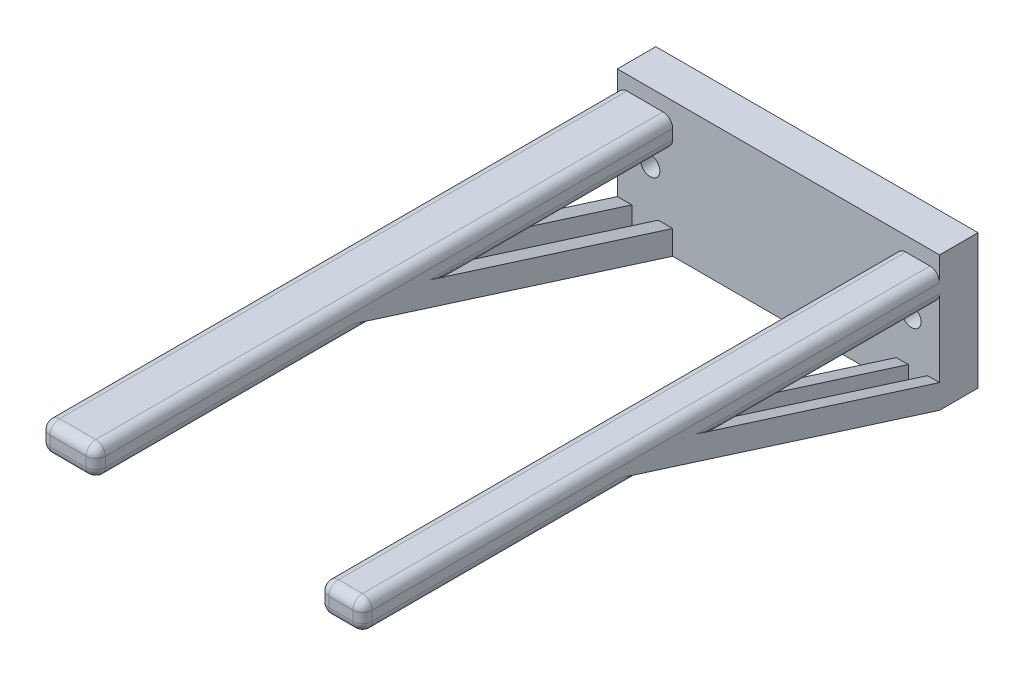
SolidWorks part; units mm, degrees
ref_plane "Plan de face" through (0, 0, 0) normal (0, 0, 1) x (1, 0, 0)
ref_plane "Plan de dessus" through (0, 0, 0) normal (0, 1, 0) x (1, 0, 0)
ref_plane "Plan de droite" through (0, 0, 0) normal (1, 0, 0) x (0, 0, -1)
sketch "Esquisse1" plane through (0, 0, 0) normal (0, 0, 1) x (1, 0, 0)
  line L1 (0, 0) -> (67, 0)
  line L2 (0, 0) -> (0, 28)
  line L3 (0, 28) -> (67, 28)
  line L4 (67, 0) -> (67, 28)
  dimension "D1" = 28
  dimension "D2" = 67
extrude "Boss.-Extru.1" add sketch "Esquisse1" along normal blind 8
sketch "Esquisse2" plane through (0, 0, 8) normal (0, 0, 1) x (1, 0, 0)
  line L0 (33.5, 29.8956) -> (33.5, -4.0759) construction
  line L5 (0, 28) -> (0, 0) construction
  line L6 (0, 14) -> (67, 14) construction
  line L12 (67, 0) -> (67, 28) construction
  line L17 (11.5, 19) -> (11.5, 25)
  line L18 (0, 25) -> (11.5, 25)
  line L19 (0, 19) -> (0, 25)
  line L20 (0, 19) -> (11.5, 19)
  line L21 (67, 25) -> (58, 25)
  line L23 (58, 25) -> (58, 19)
  line L24 (67, 19) -> (67, 25)
  line L25 (58, 19) -> (67, 19)
  line L29 (67, 28) -> (0, 28) construction
  dimension "D5" = 0
  dimension "D6" = 9
  dimension "D1" = 0
  dimension "D2" = 6
  dimension "D3" = 3
  dimension "D4" = 11.5
extrude "Boss.-Extru.2" add sketch "Esquisse2" along normal blind 120
sketch "Esquisse4" plane through (0, 0, 8) normal (0, 0, 1) x (1, 0, 0)
  line L0 (34, 28) -> (34, 4.5049) construction
  line L2 (0, 28) -> (0, 25) construction
  line L5 (67, 28) -> (0, 28) construction
  circle A0 centre (6.83, 14) radius 2
  circle A1 centre (61.17, 14) radius 2
  dimension "D2" = 27.17
  dimension "D3" = 4
  dimension "D4" = 14
  dimension "D1" = 34
extrude "Enlèv. mat.-Extru.2" cut sketch "Esquisse4" against normal blind 3
sketch "Esquisse5" plane through (0, 0, 0) normal (-1, 0, 0) x (0, 0, 1)
  line L0 (8, 0) -> (68, 19)
  line L1 (128, 19) -> (8, 19) construction
  line L3 (8, 0) -> (8, 5)
  line L4 (8, 28) -> (8, 25) construction
  line L6 (8, 5) -> (52.2105, 19)
  line L7 (52.2105, 19) -> (68, 19)
  dimension "D2" = 5
extrude "Boss.-Extru.3" add sketch "Esquisse5" against normal blind 11.5
sketch "Esquisse7" plane through (0, 0, 128) normal (0, 0, 1) x (1, 0, 0)
  line L0 (11.5, 19) -> (0, 19) construction
  line L1 (3, 19) -> (8.5, 19)
  line L2 (3, 19) -> (3, 0)
  line L3 (3, 0) -> (8.5, 0)
  line L4 (8.5, 19) -> (8.5, 0)
  line L5 (11.5, 0) -> (0, 0) construction
  line L6 (0, 0) -> (0, 19) construction
  line L7 (11.5, 0) -> (11.5, 19) construction
  dimension "D1" = 3
  dimension "D2" = 3
extrude "Enlèv. mat.-Extru.3" cut sketch "Esquisse7" against normal blind 120
sketch "Esquisse8" plane through (67, 0, 0) normal (1, 0, 0) x (0, 0, -1)
  line L0 (-8, 0) -> (-8, 5)
  line L1 (-8, 5) -> (-52.2105, 19)
  line L2 (-52.2105, 19) -> (-68, 19)
  line L3 (-128, 19) -> (-8, 19) construction
  line L4 (-68, 19) -> (-8, 0)
extrude "Boss.-Extru.4" add sketch "Esquisse8" against normal blind 9
sketch "Esquisse9" plane through (0, 0, 128) normal (0, 0, 1) x (1, 0, 0)
  line L0 (58, 19) -> (67, 19) construction
  line L1 (60.5, 19) -> (64.5, 19)
  line L2 (60.5, 19) -> (60.5, 0)
  line L3 (60.5, 0) -> (64.5, 0)
  line L4 (64.5, 19) -> (64.5, 0)
  line L5 (58, 0) -> (67, 0) construction
  line L6 (58, 19) -> (58, 0) construction
  line L7 (67, 19) -> (67, 0) construction
  dimension "D1" = 2.5
  dimension "D2" = 2.5
extrude "Enlèv. mat.-Extru.4" cut sketch "Esquisse9" against normal blind 120
fillet "Congé2" radius 2 20 edges at (0, 19, 30.1053) (58, 19, 30.1053) (11.5, 19, 30.1053) (67, 19, 30.1053) (58, 25, 68) (0, 25, 68) (11.5, 25, 68) (67, 25, 68) (62.5, 19, 128) (67, 22, 128) (62.5, 25, 128) (58, 22, 128) (11.5, 22, 128) (0, 22, 128) (5.75, 25, 128) (5.75, 19, 128) (0, 19, 98) (11.5, 19, 98) (58, 19, 98) (67, 19, 98)
equation "\"D5@Esquisse2\"=\"D1@Esquisse2\""
